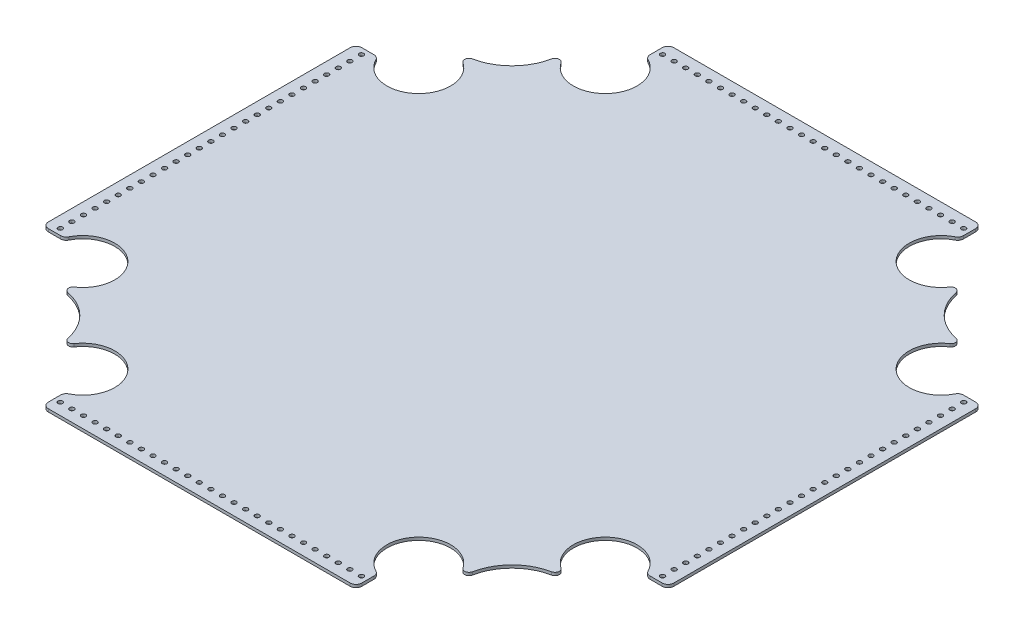
SolidWorks part; units mm, degrees
material "PC High Viscosity"
ref_plane "Front Plane" through (0, 0, 0) normal (0, 0, 1) x (1, 0, 0)
ref_plane "Top Plane" through (0, 0, 0) normal (0, 1, 0) x (1, 0, 0)
ref_plane "Right Plane" through (0, 0, 0) normal (1, 0, 0) x (0, 0, -1)
sketch "Sketch1" plane through (0, 0, 0) normal (0, 1, 0) x (1, 0, 0)
  line L1 (-342.9, -342.9) -> (342.9, -342.9)
  line L2 (-342.9, -342.9) -> (-342.9, 342.9)
  line L3 (-342.9, 342.9) -> (342.9, 342.9)
  line L4 (342.9, -342.9) -> (342.9, 342.9)
  line L5 (-342.9, -342.9) -> (342.9, 342.9) construction
  line L6 (-342.9, 342.9) -> (342.9, -342.9) construction
  point P0 (0, 0)
  dimension "D1" = 685.8
extrude "Boss-Extrude1" add sketch "Sketch1" along normal blind 3.175
sketch "Sketch3" plane through (0, 3.175, 0) normal (0, 1, 0) x (1, 0, 0)
  line L0 (-342.9, 342.9) -> (-342.9, -342.9) construction
  line L1 (342.9, 342.9) -> (-342.9, 342.9) construction
  line L2 (-171.831, 319.0652) -> (-171.831, 342.9)
  line L3 (-342.9, 171.831) -> (-319.0652, 171.831)
  line L4 (-342.9, 171.831) -> (-342.9, 342.9)
  line L5 (-342.9, 342.9) -> (-171.831, 342.9)
  line L6 (0, 342.9) -> (0, -342.9) construction
  line L7 (-342.9, -342.9) -> (342.9, -342.9) construction
  line L8 (342.9, 0) -> (-342.9, 0) construction
  line L9 (342.9, -342.9) -> (342.9, 342.9) construction
  line L10 (342.9, 342.9) -> (171.831, 342.9)
  line L11 (342.9, 171.831) -> (342.9, 342.9)
  line L12 (342.9, 171.831) -> (319.0652, 171.831)
  line L13 (171.831, 319.0652) -> (171.831, 342.9)
  line L14 (171.831, -319.0652) -> (171.831, -342.9)
  line L15 (342.9, -171.831) -> (319.0652, -171.831)
  line L16 (342.9, -171.831) -> (342.9, -342.9)
  line L17 (342.9, -342.9) -> (171.831, -342.9)
  line L18 (-342.9, -342.9) -> (-171.831, -342.9)
  line L19 (-342.9, -171.831) -> (-342.9, -342.9)
  line L20 (-342.9, -171.831) -> (-319.0652, -171.831)
  line L21 (-171.831, -319.0652) -> (-171.831, -342.9)
  arc A0 (-319.0652, 171.831) -> (-266.9153, 213.1446) centre (-286.385, 184.15) ccw
  arc A1 (-213.1446, 266.9153) -> (-171.831, 319.0652) centre (-184.15, 286.385) ccw
  arc A2 (-265.2049, 221.7663) -> (-266.9153, 213.1446) centre (-264.2604, 217.0984) ccw
  arc A3 (-213.1446, 266.9153) -> (-221.7663, 265.2049) centre (-217.0984, 264.2604) ccw
  arc A4 (-265.2049, 221.7663) -> (-221.7663, 265.2049) centre (-276.225, 276.225) ccw
  arc A5 (265.2049, 221.7663) -> (221.7663, 265.2049) centre (276.225, 276.225) cw
  arc A6 (213.1446, 266.9153) -> (221.7663, 265.2049) centre (217.0984, 264.2604) cw
  arc A7 (265.2049, 221.7663) -> (266.9153, 213.1446) centre (264.2604, 217.0984) cw
  arc A8 (213.1446, 266.9153) -> (171.831, 319.0652) centre (184.15, 286.385) cw
  arc A9 (319.0652, 171.831) -> (266.9153, 213.1446) centre (286.385, 184.15) cw
  arc A10 (319.0652, -171.831) -> (266.9153, -213.1446) centre (286.385, -184.15) ccw
  arc A11 (213.1446, -266.9153) -> (171.831, -319.0652) centre (184.15, -286.385) ccw
  arc A12 (265.2049, -221.7663) -> (266.9153, -213.1446) centre (264.2604, -217.0984) ccw
  arc A13 (213.1446, -266.9153) -> (221.7663, -265.2049) centre (217.0984, -264.2604) ccw
  arc A14 (265.2049, -221.7663) -> (221.7663, -265.2049) centre (276.225, -276.225) ccw
  arc A15 (-265.2049, -221.7663) -> (-221.7663, -265.2049) centre (-276.225, -276.225) cw
  arc A16 (-213.1446, -266.9153) -> (-221.7663, -265.2049) centre (-217.0984, -264.2604) cw
  arc A17 (-265.2049, -221.7663) -> (-266.9153, -213.1446) centre (-264.2604, -217.0984) cw
  arc A18 (-213.1446, -266.9153) -> (-171.831, -319.0652) centre (-184.15, -286.385) cw
  arc A19 (-319.0652, -171.831) -> (-266.9153, -213.1446) centre (-286.385, -184.15) cw
  dimension "D3" = 69.85
  dimension "D4" = 9.525
  dimension "D5" = 111.125
  dimension "D1" = 56.515
  dimension "D2" = 56.515
  dimension "D6" = 158.75
  dimension "D7" = 158.75
  dimension "D8" = 66.675
  dimension "D9" = 66.675
  dimension "D10" = 171.069
  dimension "D11" = 171.069
extrude "Cut-Extrude2" cut sketch "Sketch3" against normal blind 3.175
sketch "Sketch2" plane through (0, 3.175, 0) normal (0, 1, 0) x (1, 0, 0)
  line L2 (342.9, -171.831) -> (342.9, 171.831) construction
  line L3 (171.831, 342.9) -> (-171.831, 342.9) construction
  circle A0 centre (330.2, 330.2) radius 2.4892 construction
  circle A1 centre (317.5, 330.2) radius 2.4892 construction
  circle A2 centre (304.8, 330.2) radius 2.4892 construction
  circle A3 centre (292.1, 330.2) radius 2.4892 construction
  circle A4 centre (279.4, 330.2) radius 2.4892 construction
  circle A5 centre (266.7, 330.2) radius 2.4892 construction
  circle A6 centre (254, 330.2) radius 2.4892 construction
  circle A7 centre (241.3, 330.2) radius 2.4892 construction
  circle A8 centre (228.6, 330.2) radius 2.4892 construction
  circle A9 centre (215.9, 330.2) radius 2.4892 construction
  circle A10 centre (203.2, 330.2) radius 2.4892 construction
  circle A11 centre (190.5, 330.2) radius 2.4892 construction
  circle A12 centre (177.8, 330.2) radius 2.4892 construction
  circle A13 centre (165.1, 330.2) radius 2.4892
  circle A14 centre (152.4, 330.2) radius 2.4892
  circle A15 centre (139.7, 330.2) radius 2.4892
  circle A16 centre (127, 330.2) radius 2.4892
  circle A17 centre (114.3, 330.2) radius 2.4892
  circle A18 centre (101.6, 330.2) radius 2.4892
  circle A19 centre (88.9, 330.2) radius 2.4892
  circle A20 centre (76.2, 330.2) radius 2.4892
  circle A21 centre (63.5, 330.2) radius 2.4892
  circle A22 centre (50.8, 330.2) radius 2.4892
  circle A23 centre (38.1, 330.2) radius 2.4892
  circle A24 centre (25.4, 330.2) radius 2.4892
  circle A25 centre (12.7, 330.2) radius 2.4892
  circle A26 centre (0, 330.2) radius 2.4892
  circle A27 centre (-12.7, 330.2) radius 2.4892
  circle A28 centre (-25.4, 330.2) radius 2.4892
  circle A29 centre (-38.1, 330.2) radius 2.4892
  circle A30 centre (-50.8, 330.2) radius 2.4892
  circle A31 centre (-63.5, 330.2) radius 2.4892
  circle A32 centre (-76.2, 330.2) radius 2.4892
  circle A33 centre (-88.9, 330.2) radius 2.4892
  circle A34 centre (-101.6, 330.2) radius 2.4892
  circle A35 centre (-114.3, 330.2) radius 2.4892
  circle A36 centre (-127, 330.2) radius 2.4892
  circle A37 centre (-139.7, 330.2) radius 2.4892
  circle A38 centre (-152.4, 330.2) radius 2.4892
  circle A39 centre (-165.1, 330.2) radius 2.4892
  circle A40 centre (-177.8, 330.2) radius 2.4892 construction
  circle A41 centre (-190.5, 330.2) radius 2.4892 construction
  circle A42 centre (-203.2, 330.2) radius 2.4892 construction
  circle A43 centre (-215.9, 330.2) radius 2.4892 construction
  circle A44 centre (-228.6, 330.2) radius 2.4892 construction
  circle A45 centre (-241.3, 330.2) radius 2.4892 construction
  circle A46 centre (-254, 330.2) radius 2.4892 construction
  circle A47 centre (-266.7, 330.2) radius 2.4892 construction
  circle A48 centre (-279.4, 330.2) radius 2.4892 construction
  circle A49 centre (-292.1, 330.2) radius 2.4892 construction
  circle A50 centre (-304.8, 330.2) radius 2.4892 construction
  circle A51 centre (-317.5, 330.2) radius 2.4892 construction
  circle A52 centre (-330.2, 330.2) radius 2.4892 construction
  circle A289 centre (-330.2, 317.5) radius 2.4892 construction
  circle A290 centre (-330.2, 304.8) radius 2.4892 construction
  circle A291 centre (-330.2, 292.1) radius 2.4892 construction
  circle A292 centre (-330.2, 279.4) radius 2.4892 construction
  circle A293 centre (-330.2, 266.7) radius 2.4892 construction
  circle A294 centre (-330.2, 254) radius 2.4892 construction
  circle A295 centre (-330.2, 241.3) radius 2.4892 construction
  circle A296 centre (-330.2, 228.6) radius 2.4892 construction
  circle A297 centre (-330.2, 215.9) radius 2.4892 construction
  circle A298 centre (-330.2, 203.2) radius 2.4892 construction
  circle A299 centre (-330.2, 190.5) radius 2.4892 construction
  circle A300 centre (-330.2, 177.8) radius 2.4892 construction
  circle A301 centre (-330.2, 165.1) radius 2.4892
  circle A302 centre (-330.2, 152.4) radius 2.4892
  circle A303 centre (-330.2, 139.7) radius 2.4892
  circle A304 centre (-330.2, 127) radius 2.4892
  circle A305 centre (-330.2, 114.3) radius 2.4892
  circle A306 centre (-330.2, 101.6) radius 2.4892
  circle A307 centre (-330.2, 88.9) radius 2.4892
  circle A308 centre (-330.2, 76.2) radius 2.4892
  circle A309 centre (-330.2, 63.5) radius 2.4892
  circle A310 centre (-330.2, 50.8) radius 2.4892
  circle A311 centre (-330.2, 38.1) radius 2.4892
  circle A312 centre (-330.2, 25.4) radius 2.4892
  circle A313 centre (-330.2, 12.7) radius 2.4892
  circle A314 centre (-330.2, 0) radius 2.4892
  circle A315 centre (-330.2, -12.7) radius 2.4892
  circle A316 centre (-330.2, -25.4) radius 2.4892
  circle A317 centre (-330.2, -38.1) radius 2.4892
  circle A318 centre (-330.2, -50.8) radius 2.4892
  circle A319 centre (-330.2, -63.5) radius 2.4892
  circle A320 centre (-330.2, -76.2) radius 2.4892
  circle A321 centre (-330.2, -88.9) radius 2.4892
  circle A322 centre (-330.2, -101.6) radius 2.4892
  circle A323 centre (-330.2, -114.3) radius 2.4892
  circle A324 centre (-330.2, -127) radius 2.4892
  circle A325 centre (-330.2, -139.7) radius 2.4892
  circle A326 centre (-330.2, -152.4) radius 2.4892
  circle A327 centre (-330.2, -165.1) radius 2.4892
  circle A328 centre (-330.2, -177.8) radius 2.4892 construction
  circle A329 centre (-330.2, -190.5) radius 2.4892 construction
  circle A330 centre (-330.2, -203.2) radius 2.4892 construction
  circle A331 centre (-330.2, -215.9) radius 2.4892 construction
  circle A332 centre (-330.2, -228.6) radius 2.4892 construction
  circle A333 centre (-330.2, -241.3) radius 2.4892 construction
  circle A334 centre (-330.2, -254) radius 2.4892 construction
  circle A335 centre (-330.2, -266.7) radius 2.4892 construction
  circle A336 centre (-330.2, -279.4) radius 2.4892 construction
  circle A337 centre (-330.2, -292.1) radius 2.4892 construction
  circle A338 centre (-330.2, -304.8) radius 2.4892 construction
  circle A339 centre (-330.2, -317.5) radius 2.4892 construction
  circle A340 centre (-330.2, -330.2) radius 2.4892 construction
  circle A341 centre (-317.5, -330.2) radius 2.4892 construction
  circle A342 centre (-304.8, -330.2) radius 2.4892 construction
  circle A343 centre (-292.1, -330.2) radius 2.4892 construction
  circle A344 centre (-279.4, -330.2) radius 2.4892 construction
  circle A345 centre (-266.7, -330.2) radius 2.4892 construction
  circle A346 centre (-254, -330.2) radius 2.4892 construction
  circle A347 centre (-241.3, -330.2) radius 2.4892 construction
  circle A348 centre (-228.6, -330.2) radius 2.4892 construction
  circle A349 centre (-215.9, -330.2) radius 2.4892 construction
  circle A350 centre (-203.2, -330.2) radius 2.4892 construction
  circle A351 centre (-190.5, -330.2) radius 2.4892 construction
  circle A352 centre (-177.8, -330.2) radius 2.4892 construction
  circle A353 centre (-165.1, -330.2) radius 2.4892
  circle A354 centre (-152.4, -330.2) radius 2.4892
  circle A355 centre (-139.7, -330.2) radius 2.4892
  circle A356 centre (-127, -330.2) radius 2.4892
  circle A357 centre (-114.3, -330.2) radius 2.4892
  circle A358 centre (-101.6, -330.2) radius 2.4892
  circle A359 centre (-88.9, -330.2) radius 2.4892
  circle A360 centre (-76.2, -330.2) radius 2.4892
  circle A361 centre (-63.5, -330.2) radius 2.4892
  circle A362 centre (-50.8, -330.2) radius 2.4892
  circle A363 centre (-38.1, -330.2) radius 2.4892
  circle A364 centre (-25.4, -330.2) radius 2.4892
  circle A365 centre (-12.7, -330.2) radius 2.4892
  circle A366 centre (0, -330.2) radius 2.4892
  circle A367 centre (12.7, -330.2) radius 2.4892
  circle A368 centre (25.4, -330.2) radius 2.4892
  circle A369 centre (38.1, -330.2) radius 2.4892
  circle A370 centre (50.8, -330.2) radius 2.4892
  circle A371 centre (63.5, -330.2) radius 2.4892
  circle A372 centre (76.2, -330.2) radius 2.4892
  circle A373 centre (88.9, -330.2) radius 2.4892
  circle A374 centre (101.6, -330.2) radius 2.4892
  circle A375 centre (114.3, -330.2) radius 2.4892
  circle A376 centre (127, -330.2) radius 2.4892
  circle A377 centre (139.7, -330.2) radius 2.4892
  circle A378 centre (152.4, -330.2) radius 2.4892
  circle A379 centre (165.1, -330.2) radius 2.4892
  circle A380 centre (177.8, -330.2) radius 2.4892 construction
  circle A381 centre (190.5, -330.2) radius 2.4892 construction
  circle A382 centre (203.2, -330.2) radius 2.4892 construction
  circle A383 centre (215.9, -330.2) radius 2.4892 construction
  circle A384 centre (228.6, -330.2) radius 2.4892 construction
  circle A385 centre (241.3, -330.2) radius 2.4892 construction
  circle A386 centre (254, -330.2) radius 2.4892 construction
  circle A387 centre (266.7, -330.2) radius 2.4892 construction
  circle A388 centre (279.4, -330.2) radius 2.4892 construction
  circle A389 centre (292.1, -330.2) radius 2.4892 construction
  circle A390 centre (304.8, -330.2) radius 2.4892 construction
  circle A391 centre (317.5, -330.2) radius 2.4892 construction
  circle A392 centre (330.2, -330.2) radius 2.4892 construction
  circle A393 centre (330.2, -317.5) radius 2.4892 construction
  circle A394 centre (330.2, -304.8) radius 2.4892 construction
  circle A395 centre (330.2, -292.1) radius 2.4892 construction
  circle A396 centre (330.2, -279.4) radius 2.4892 construction
  circle A397 centre (330.2, -266.7) radius 2.4892 construction
  circle A398 centre (330.2, -254) radius 2.4892 construction
  circle A399 centre (330.2, -241.3) radius 2.4892 construction
  circle A400 centre (330.2, -228.6) radius 2.4892 construction
  circle A401 centre (330.2, -215.9) radius 2.4892 construction
  circle A402 centre (330.2, -203.2) radius 2.4892 construction
  circle A403 centre (330.2, -190.5) radius 2.4892 construction
  circle A404 centre (330.2, -177.8) radius 2.4892 construction
  circle A405 centre (330.2, -165.1) radius 2.4892
  circle A406 centre (330.2, -152.4) radius 2.4892
  circle A407 centre (330.2, -139.7) radius 2.4892
  circle A408 centre (330.2, -127) radius 2.4892
  circle A409 centre (330.2, -114.3) radius 2.4892
  circle A410 centre (330.2, -101.6) radius 2.4892
  circle A411 centre (330.2, -88.9) radius 2.4892
  circle A412 centre (330.2, -76.2) radius 2.4892
  circle A413 centre (330.2, -63.5) radius 2.4892
  circle A414 centre (330.2, -50.8) radius 2.4892
  circle A415 centre (330.2, -38.1) radius 2.4892
  circle A416 centre (330.2, -25.4) radius 2.4892
  circle A417 centre (330.2, -12.7) radius 2.4892
  circle A418 centre (330.2, 0) radius 2.4892
  circle A419 centre (330.2, 12.7) radius 2.4892
  circle A420 centre (330.2, 25.4) radius 2.4892
  circle A421 centre (330.2, 38.1) radius 2.4892
  circle A422 centre (330.2, 50.8) radius 2.4892
  circle A423 centre (330.2, 63.5) radius 2.4892
  circle A424 centre (330.2, 76.2) radius 2.4892
  circle A425 centre (330.2, 88.9) radius 2.4892
  circle A426 centre (330.2, 101.6) radius 2.4892
  circle A427 centre (330.2, 114.3) radius 2.4892
  circle A428 centre (330.2, 127) radius 2.4892
  circle A429 centre (330.2, 139.7) radius 2.4892
  circle A430 centre (330.2, 152.4) radius 2.4892
  circle A431 centre (330.2, 165.1) radius 2.4892
  circle A432 centre (330.2, 177.8) radius 2.4892 construction
  circle A433 centre (330.2, 190.5) radius 2.4892 construction
  circle A434 centre (330.2, 203.2) radius 2.4892 construction
  circle A435 centre (330.2, 215.9) radius 2.4892 construction
  circle A436 centre (330.2, 228.6) radius 2.4892 construction
  circle A437 centre (330.2, 241.3) radius 2.4892 construction
  circle A438 centre (330.2, 254) radius 2.4892 construction
  circle A439 centre (330.2, 266.7) radius 2.4892 construction
  circle A440 centre (330.2, 279.4) radius 2.4892 construction
  circle A441 centre (330.2, 292.1) radius 2.4892 construction
  circle A442 centre (330.2, 304.8) radius 2.4892 construction
  circle A443 centre (330.2, 317.5) radius 2.4892 construction
  dimension "D1" = 12.7
  dimension "D2" = 12.7
  dimension "D3" = 4.9784
  dimension "D5" = 12.7
  dimension "D7" = 12.7
  dimension "D9" = 12.7
  dimension "D11" = 12.7
  dimension "D4" = 53
  dimension "D6" = 53
  dimension "D8" = 53
  dimension "D10" = 52
extrude "Cut-Extrude1" cut sketch "Sketch2" against normal blind 3.175
fillet "Fillet1" radius 6.35 16 edges at (-171.831, 1.5875, 342.9) (171.831, 1.5875, 342.9) (171.831, 1.5875, 319.0652) (319.0652, 1.5875, 171.831) (342.9, 1.5875, 171.831) (342.9, 1.5875, -171.831) (319.0652, 1.5875, -171.831) (171.831, 1.5875, -319.0652) (171.831, 1.5875, -342.9) (-171.831, 1.5875, -319.0652) (-319.0652, 1.5875, -171.831) (-342.9, 1.5875, -171.831) (-342.9, 1.5875, 171.831) (-319.0652, 1.5875, 171.831) (-171.831, 1.5875, 319.0652) (-171.831, 1.5875, -342.9)
